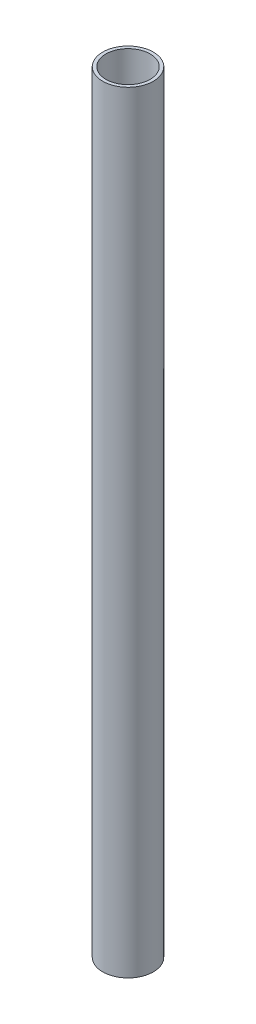
SolidWorks part; units mm, degrees
ref_plane "Front Plane" through (0, 0, 0) normal (0, 0, 1) x (1, 0, 0)
ref_plane "Top Plane" through (0, 0, 0) normal (0, 1, 0) x (1, 0, 0)
ref_plane "Right Plane" through (0, 0, 0) normal (1, 0, 0) x (0, 0, -1)
sketch "Sketch1" plane through (195.4321, -85.7114, -1333.2384) normal (0, 1, 0) x (0.656, 0, 0.7547)
  circle A0 centre (102.4089, 86.292) radius 17.4625
  circle A1 centre (102.4089, 86.292) radius 20.0025
  dimension "D1" = 34.925
  dimension "D2" = 2.54
extrude "Boss-Extrude1" add sketch "Sketch1" along normal blind 609.6
